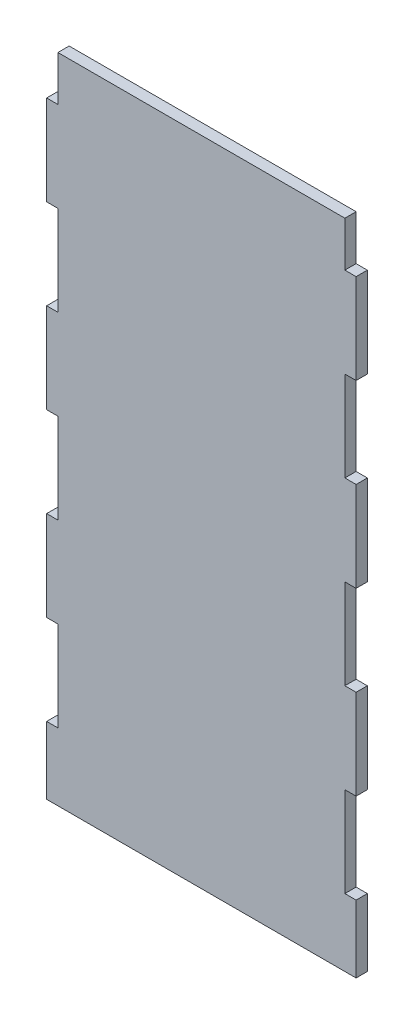
SolidWorks part; units mm, degrees
material "Acrylic (Medium-high impact)"
ref_plane "Front Plane" through (0, 0, 0) normal (0, 0, 1) x (1, 0, 0)
ref_plane "Top Plane" through (0, 0, 0) normal (0, 1, 0) x (1, 0, 0)
ref_plane "Right Plane" through (0, 0, 0) normal (1, 0, 0) x (0, 0, -1)
sketch "Sketch1" plane through (0, 0, 0) normal (0, 0, 1) x (1, 0, 0)
  line L0 (0, 139.7) -> (-3.175, 139.7)
  line L1 (0, 0) -> (0, -12.7)
  line L2 (0, 0) -> (0, 12.7)
  line L3 (0, 152.4) -> (81, 152.4)
  line L4 (81, -12.7) -> (84.175, -12.7)
  line L5 (-3.175, 139.7) -> (-3.175, 114.3)
  line L6 (-3.175, 114.3) -> (0, 114.3)
  line L7 (-3.175, -31.75) -> (84.175, -31.75)
  line L8 (-3.175, -12.7) -> (-3.175, -31.75)
  line L9 (84.175, -12.7) -> (84.175, -31.75)
  line L10 (81, 38.1) -> (84.175, 38.1)
  line L11 (84.175, 38.1) -> (84.175, 12.7)
  line L13 (40.5, 152.4) -> (40.5, -31.75) construction
  line L14 (84.175, 12.7) -> (81, 12.7)
  line L15 (81, 88.9) -> (84.175, 88.9)
  line L16 (84.175, 88.9) -> (84.175, 63.5)
  line L17 (84.175, 63.5) -> (81, 63.5)
  line L18 (81, 38.1) -> (81, 63.5)
  line L19 (81, 88.9) -> (81, 114.3)
  line L20 (81, 139.7) -> (81, 152.4)
  line L22 (84.175, 114.3) -> (81, 114.3)
  line L23 (0, 139.7) -> (0, 152.4)
  line L24 (0, 88.9) -> (0, 114.3)
  line L25 (0, 38.1) -> (0, 63.5)
  line L26 (84.175, 139.7) -> (84.175, 114.3)
  line L27 (81, 0) -> (81, 12.7)
  line L28 (81, 0) -> (81, -12.7)
  line L29 (-3.175, 63.5) -> (0, 63.5)
  line L30 (-3.175, 88.9) -> (-3.175, 63.5)
  line L31 (0, 88.9) -> (-3.175, 88.9)
  line L32 (-3.175, 12.7) -> (0, 12.7)
  line L33 (-3.175, 38.1) -> (-3.175, 12.7)
  line L34 (0, 38.1) -> (-3.175, 38.1)
  line L37 (0, -12.7) -> (-3.175, -12.7)
  line L38 (81, 139.7) -> (84.175, 139.7)
  line L39 (-3.175, -38.1) -> (0, -38.1) [skipped]
  line L40 (-3.175, -12.7) -> (-3.175, -38.1) [skipped]
  dimension "D1" = 81
  dimension "D2" = 19.05
  dimension "D3" = 25.4
  dimension "D4" = 12.7
  dimension "D5" = 3.175
  dimension "D7" = 25.4
  dimension "D8" = 12.7
  dimension "D6" = 4
extrude "Boss-Extrude1" add sketch "Sketch1" along normal blind 3.175
